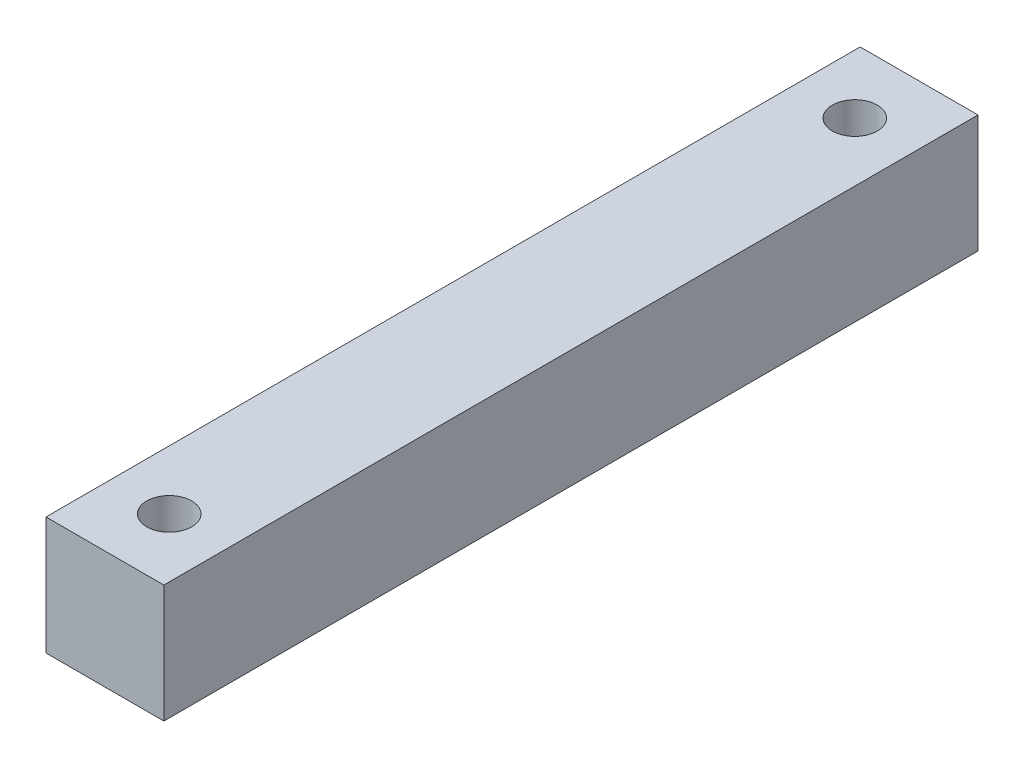
SolidWorks part; units mm, degrees
material "ﾁｰｸ材"
ref_plane "正面" through (0, 0, 0) normal (0, 0, 1) x (1, 0, 0)
ref_plane "平面" through (0, 0, 0) normal (0, 1, 0) x (1, 0, 0)
ref_plane "右側面" through (0, 0, 0) normal (1, 0, 0) x (0, 0, -1)
sketch "ｽｹｯﾁ1" plane through (0, 0, 0) normal (0, 0, 1) x (1, 0, 0)
  line L1 (2.75, 2.75) -> (-2.75, 2.75)
  line L2 (2.75, 2.75) -> (2.75, -2.75)
  line L3 (2.75, -2.75) -> (-2.75, -2.75)
  line L4 (-2.75, 2.75) -> (-2.75, -2.75)
  line L5 (2.75, 2.75) -> (-2.75, -2.75) construction
  line L6 (2.75, -2.75) -> (-2.75, 2.75) construction
  point P0 (0, 0)
  dimension "D1" = 5.5
  dimension "D2" = 5.5
extrude "ﾎﾞｽ - 押し出し1" add sketch "ｽｹｯﾁ1" along normal blind 38
sketch "ｽｹｯﾁ2" plane through (0, 2.75, 0) normal (0, 1, 0) x (1, 0, 0)
  line L0 (-2.75, -19) -> (2.75, -19) construction
  line L1 (-2.75, -38) -> (-2.75, 0) construction
  line L2 (2.75, -38) -> (2.75, 0) construction
  circle A0 centre (0, -3) radius 1.05
  circle A1 centre (0, -35) radius 1.05
  point P10 (0, -35)
  dimension "D1" = 2.1
  dimension "D2" = 16
  dimension "D3" = 16
extrude "ｶｯﾄ - 押し出し1" cut sketch "ｽｹｯﾁ2" against normal blind 5.5
